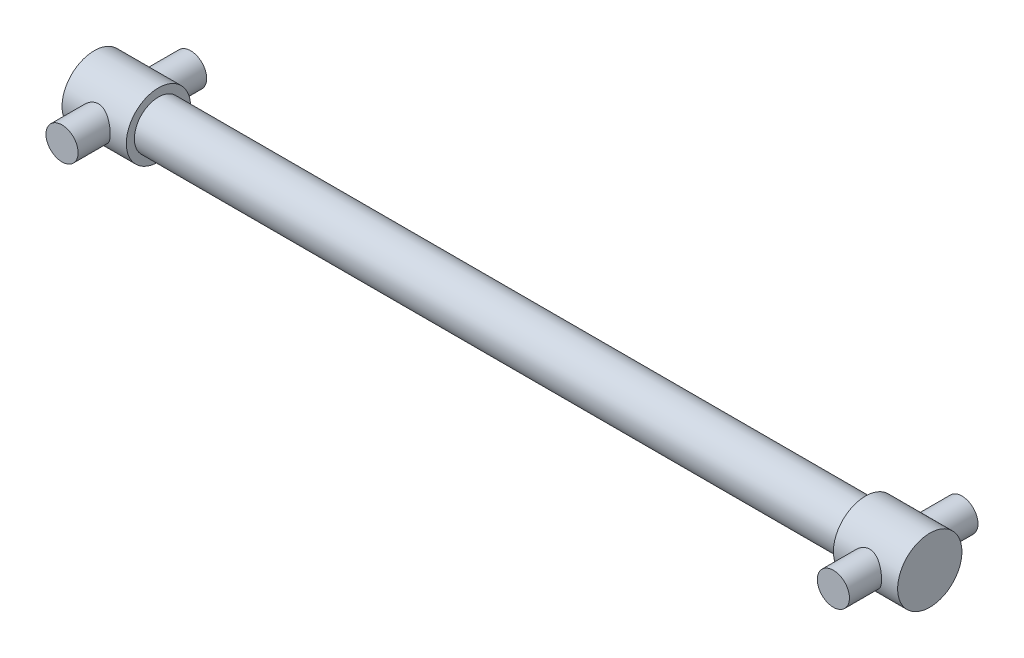
SolidWorks part; units mm, degrees
material "AISI 304"
ref_plane "Front" through (0, 0, 0) normal (0, 0, 1) x (1, 0, 0)
ref_plane "Top" through (0, 0, 0) normal (0, 1, 0) x (1, 0, 0)
ref_plane "Right" through (0, 0, 0) normal (1, 0, 0) x (0, 0, -1)
sketch "Sketch1" plane through (0, 0, 0) normal (1, 0, 0) x (0, 0, -1)
  circle A0 centre (0, 0) radius 1.5
  dimension "D1" = 3
extrude "Boss-Extrude1" add sketch "Sketch1" along normal blind 52
sketch "Sketch2" plane through (52, 0, 0) normal (1, 0, 0) x (0, 0, -1)
  circle A0 centre (0, 0) radius 2
  dimension "D1" = 4
extrude "Boss-Extrude2" add sketch "Sketch2" against normal blind 4
sketch "Sketch3" plane through (0, 0, 0) normal (-1, 0, 0) x (0, 0, 1)
  circle A0 centre (0, 0) radius 2
  dimension "D1" = 4
extrude "Boss-Extrude3" add sketch "Sketch3" against normal blind 4
ref_plane "Plane1" through (0, 0, 2) normal (0, 0, 1) x (1, 0, 0)
sketch "Sketch4" plane through (0, 0, 2) normal (0, 0, 1) x (1, 0, 0)
  line L0 (52, -2) -> (52, 2) construction
  circle A0 centre (50, 0) radius 1
  circle A1 centre (2, 0) radius 1
  dimension "D1" = 2
  dimension "D2" = 2
  dimension "D3" = 2
extrude "Boss-Extrude4" add sketch "Sketch4" along normal blind 2 and the other way blind 6
